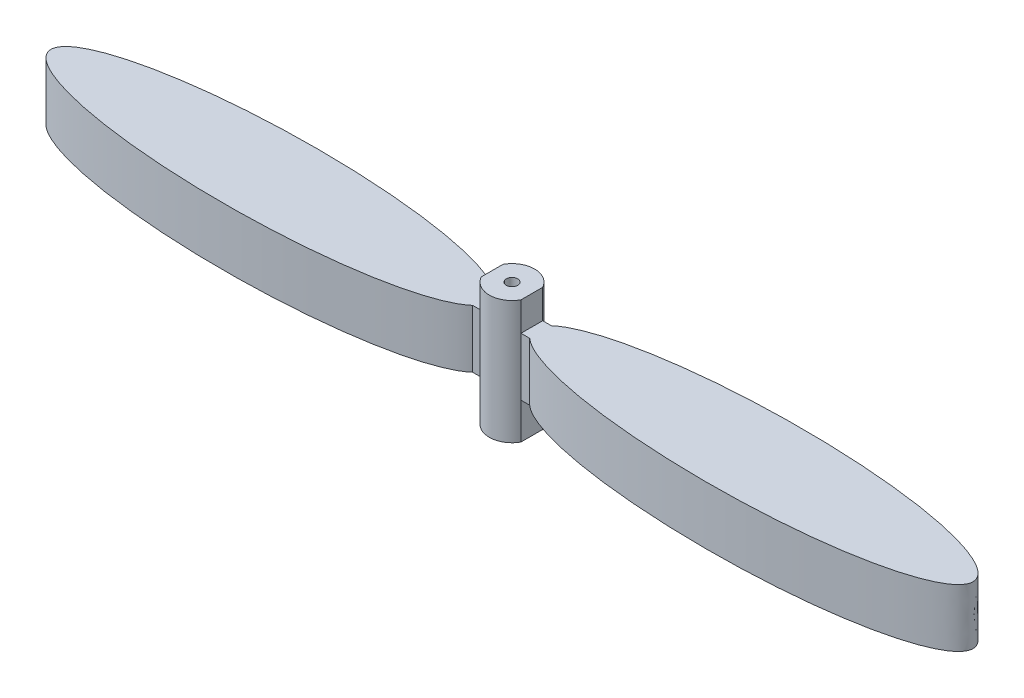
SolidWorks part; units mm, degrees
ref_plane "Front Plane" through (0, 0, 0) normal (0, 0, 1) x (1, 0, 0)
ref_plane "Top Plane" through (0, 0, 0) normal (0, 1, 0) x (1, 0, 0)
ref_plane "Right Plane" through (0, 0, 0) normal (1, 0, 0) x (0, 0, -1)
sketch "Sketch1" plane through (0, 0, 0) normal (0, 1, 0) x (1, 0, 0)
  line L0 (0, -42.5238) -> (0, 49.4273) construction
  line L1 (-5.4829, -3) -> (-7.883, -3)
  line L2 (7.883, -3) -> (5.4829, -3)
  line L3 (-5.4829, 3) -> (-7.883, 3)
  line L4 (7.883, 3) -> (5.4829, 3)
  circle A0 centre (0, 0) radius 1.575
  arc A1 (-5.4829, -3) -> (5.4829, -3) centre (0, 0) ccw
  arc A2 (5.4829, 3) -> (-5.4829, 3) centre (0, 0) ccw
  ellipse E0 centre (-66.75, 0) end of major axis (-6.25, 0) minor radius 13 (-7.883, 3) -> (-7.883, -3) ccw
  ellipse E1 centre (66.75, 0) end of major axis (127.25, 0) minor radius 13 (7.883, 3) -> (7.883, -3) cw
  point P7 (-6.25, 0)
  dimension "D1" = 3.15
  dimension "D2" = 12.5
  dimension "D3" = 121
  dimension "D4" = 26
  dimension "D5" = 3
  dimension "D6" = 3
extrude "Boss-Extrude1" add sketch "Sketch1" along normal blind 34
sketch "Sketch2" plane through (0, 0, 0) normal (0, 0, 1) x (1, 0, 0)
  line L0 (-127.25, 34) -> (-127.25, 0) construction
  line L1 (-5.4829, 0) -> (-127.25, 0)
  line L2 (-5.4829, 0) -> (-5.4829, 10)
  line L3 (-5.4829, 10) -> (-127.25, 10)
  line L4 (-127.25, 0) -> (-127.25, 10)
  line L5 (-5.4829, 34) -> (-5.4829, 0) construction
  line L6 (-5.4829, 26) -> (-127.25, 26)
  line L7 (-5.4829, 26) -> (-5.4829, 34)
  line L8 (-5.4829, 34) -> (-127.25, 34)
  line L9 (-127.25, 26) -> (-127.25, 34)
  line L10 (127.25, 0) -> (127.25, 34) construction
  line L11 (5.4829, 34) -> (127.25, 34)
  line L12 (5.4829, 34) -> (5.4829, 26)
  line L13 (5.4829, 26) -> (127.25, 26)
  line L14 (127.25, 34) -> (127.25, 26)
  line L16 (127.25, 10) -> (5.4829, 10)
  line L17 (127.25, 10) -> (127.25, 0)
  line L18 (127.25, 0) -> (5.4829, 0)
  line L19 (5.4829, 10) -> (5.4829, 0)
  dimension "D1" = 10
  dimension "D2" = 8
  dimension "D3" = 8
  dimension "D4" = 10
extrude "Cut-Extrude1" cut sketch "Sketch2" against normal mid plane 34
sketch "Sketch3" plane through (0, 0, 0) normal (0, 1, 0) x (1, 0, 0)
  circle A0 centre (0, 0) radius 127.25
  circle A1 centre (0, 0) radius 126.25
  ellipse E0 centre (-66.75, 0) end of major axis (-127.25, 0) minor radius 13 (-7.883, 3) -> (-7.883, -3) ccw construction
  dimension "D1" = 1
extrude "Boss-Extrude2" [suppressed] add sketch "Sketch3" along normal up to vertex
